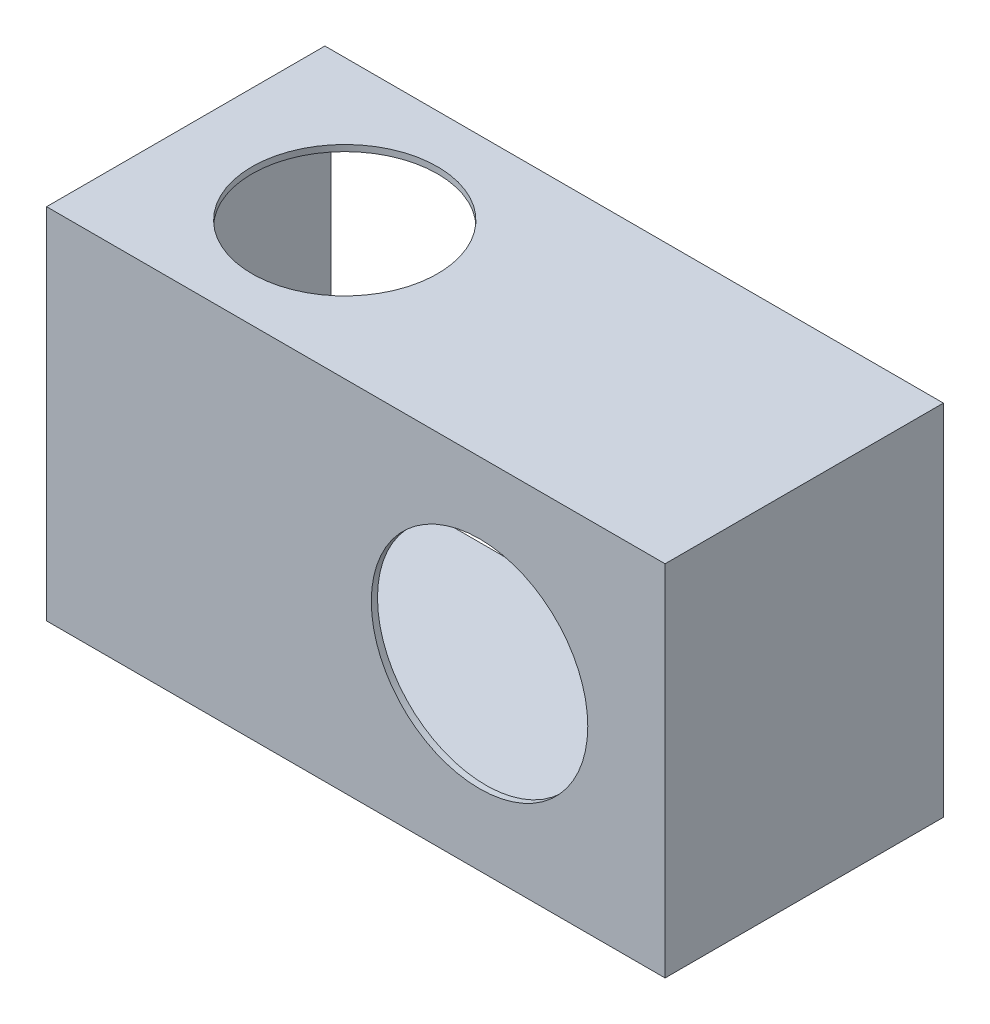
SolidWorks part; units mm, degrees
ref_plane "Front Plane" through (0, 0, 0) normal (0, 0, 1) x (1, 0, 0)
ref_plane "Top Plane" through (0, 0, 0) normal (0, 1, 0) x (1, 0, 0)
ref_plane "Right Plane" through (0, 0, 0) normal (1, 0, 0) x (0, 0, -1)
sketch "Sketch1" plane through (0, 0, 0) normal (0, 0, 1) x (1, 0, 0)
  line L1 (-23.2522, -234.0557) -> (-223.2522, -234.0557)
  line L2 (-23.2522, -234.0557) -> (-23.2522, -118.0557)
  line L3 (-23.2522, -118.0557) -> (-223.2522, -118.0557)
  line L4 (-223.2522, -234.0557) -> (-223.2522, -118.0557)
  dimension "D1" = 200
  dimension "D2" = 116
extrude "Boss-Extrude1" add sketch "Sketch1" along normal blind 90 contours L3 L4 L1 L2
shell "Shell1" thickness 2
sketch "Sketch2" plane through (0, 0, 88) normal (0, 0, -1) x (-1, 0, 0)
  line L0 (23.2522, -176.0557) -> (223.2522, -176.0557) construction
  line L1 (23.2522, -234.0557) -> (23.2522, -118.0557) construction
  line L2 (223.2522, -234.0557) -> (223.2522, -118.0557) construction
  line L3 (123.2522, -176.0557) -> (123.2522, -93.3399) construction
  circle A0 centre (83.2522, -176.0557) radius 35
  dimension "D1" = 70
  dimension "D2" = 40
extrude "Cut-Extrude1" cut sketch "Sketch2" against normal blind 10
sketch "Sketch3" plane through (0, -118.0557, 0) normal (0, 1, 0) x (1, 0, 0)
  circle A0 centre (-171.2554, -45.5792) radius 30
extrude "Cut-Extrude2" cut sketch "Sketch3" against normal blind 10
